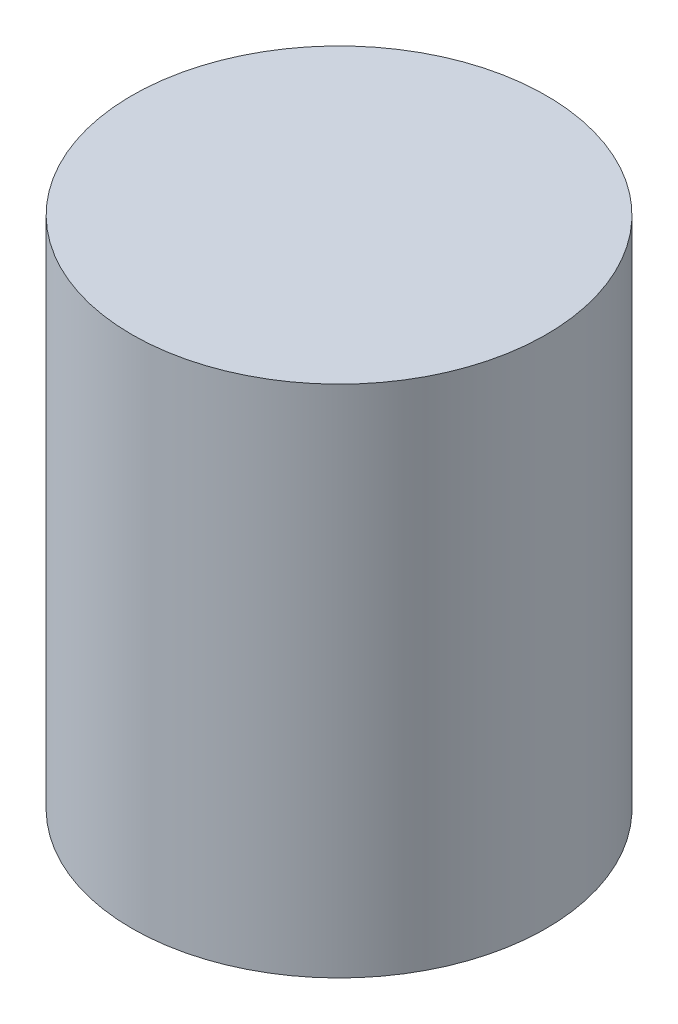
SolidWorks part; units mm, degrees
ref_plane "Front Plane" through (0, 0, 0) normal (0, 0, 1) x (1, 0, 0)
ref_plane "Top Plane" through (0, 0, 0) normal (0, 1, 0) x (1, 0, 0)
ref_plane "Right Plane" through (0, 0, 0) normal (1, 0, 0) x (0, 0, -1)
sketch "Sketch1" plane through (0, 0, 0) normal (0, 1, 0) x (1, 0, 0)
  circle A0 centre (0, 0) radius 29
extrude "Motor_Envelope" add sketch "Sketch1" along normal blind 72
equation "\"ValveDiameter\" = 50mm"
equation "\"MotorGearTeeth\" = 40"
equation "\"OutputGearTeeth\" = 80"
equation "\"GearModule\" = 1.5mm"
equation "\"PressureAngle\" = 20deg"
equation "\"GearCenterDistance\" = 90mm"
equation "\"GearWidth\" = 18mm"
equation "\"OutputShaftDiameter\" = 20mm"
equation "\"BearingOD\" = 47mm"
equation "\"BearingWidth\" = 14mm"
equation "\"PlateThickness\" = 6mm"
equation "\"ValveRotation\" = 90deg"
